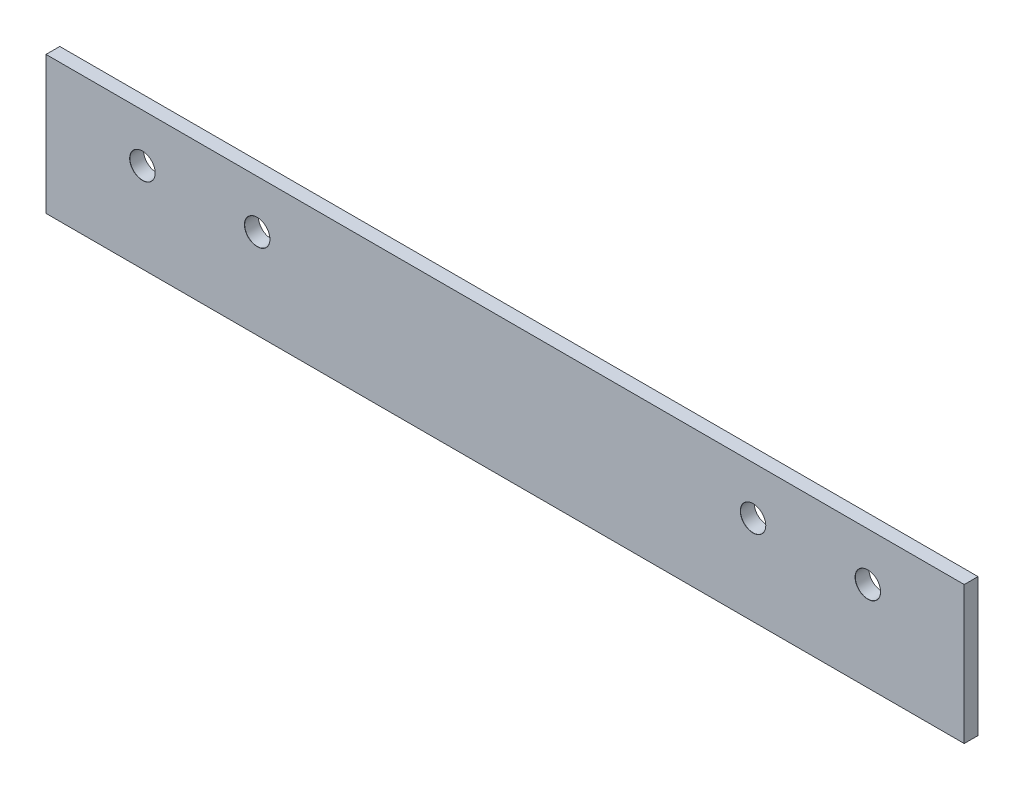
SolidWorks part; units mm, degrees
ref_plane "Front Plane" through (0, 0, 0) normal (0, 0, 1) x (1, 0, 0)
ref_plane "Top Plane" through (0, 0, 0) normal (0, 1, 0) x (1, 0, 0)
ref_plane "Right Plane" through (0, 0, 0) normal (1, 0, 0) x (0, 0, -1)
sketch "Sketch1" plane through (0, 0, 0) normal (0, 0, 1) x (1, 0, 0)
  line L1 (100, 15) -> (-100, 15)
  line L2 (100, 15) -> (100, -15)
  line L3 (100, -15) -> (-100, -15)
  line L4 (-100, 15) -> (-100, -15)
  line L5 (100, 15) -> (-100, -15) construction
  line L6 (100, -15) -> (-100, 15) construction
  point P0 (0, 0)
  dimension "D1" = 30
  dimension "D2" = 200
extrude "Boss-Extrude1" add sketch "Sketch1" along normal mid plane 3
sketch "Sketch2" plane through (0, 0, 1.5) normal (0, 0, 1) x (1, 0, 0)
  line L0 (0, 44.2468) -> (0, -56.7953) construction
  line L1 (-79, 4.5) -> (-54, 4.5) construction
  line L2 (100, 15) -> (-100, 15) construction
  line L3 (-100, 15) -> (-100, -15) construction
  line L4 (79, 4.5) -> (54, 4.5) construction
  point P3 (-79, 4.5)
  point P4 (-54, 4.5)
  point P9 (79, 4.5)
  point P10 (54, 4.5)
  dimension "D1" = 10.5
  dimension "D2" = 25
  dimension "D3" = 21
hole_wizard "M5 Clearance Hole1" positions "Sketch2" profile "Sketch3" hole size "M5" standard "ISO" end condition through all
sketch "Sketch3" plane through (54, 4.5, 1.5) normal (1, 0, 0) x (0, -1, 0)
  line L0 (0, 0) -> (0, 3)
  line L1 (0, 3) -> (2.75, 3)
  line L2 (2.75, 3) -> (2.75, 0.025)
  line L3 (2.75, 0.025) -> (2.775, 0)
  line L5 (2.775, 0) -> (0, 0)
  line L6 (-2.75, 0.025) -> (-2.775, 0) construction
  line L11 (0, -6.35) -> (0, 107.95) construction
  dimension "Thru Hole Dia." = 5.5
  dimension "Thru Hole Depth" = 3
  dimension "Near C'Sink Dia." = 5.55
  dimension "Near C'Sink Angle" = 90
sketch "Sketch4" plane through (0, 0, 0) normal (0, 0, 1) x (1, 0, 0)
  line L1 (-100, 15) -> (-115, 15)
  line L2 (-100, 15) -> (-100, -15)
  line L3 (-100, -15) -> (-115, -15)
  line L4 (-115, 15) -> (-115, -15)
  dimension "D1" = 15
extrude "Boss-Extrude2" [suppressed] add sketch "Sketch4" along normal mid plane 3
